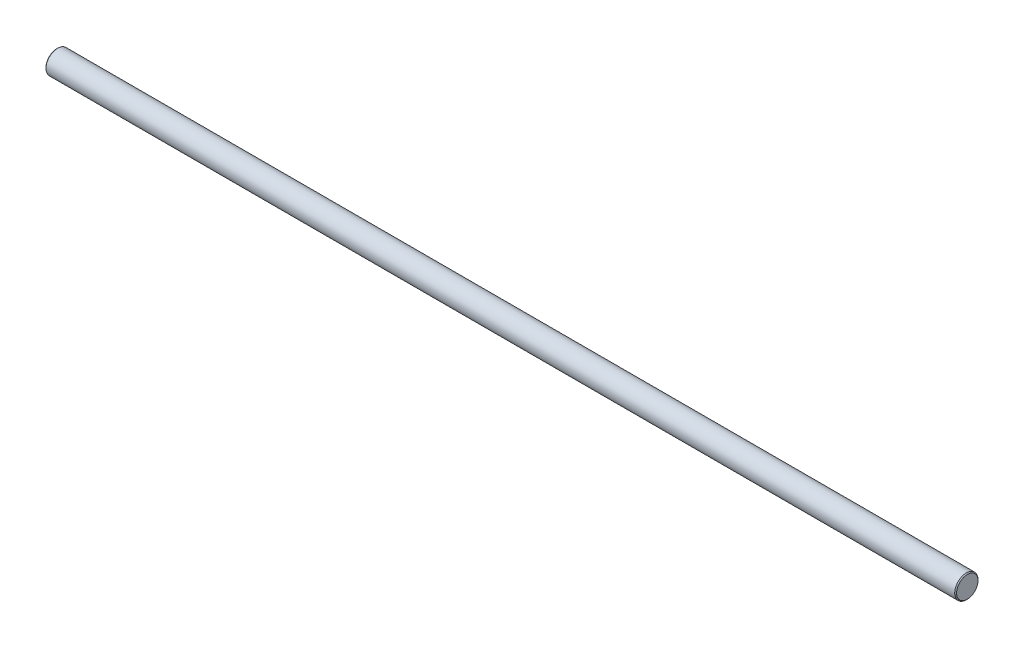
SolidWorks part; units mm, degrees
material "Alloy Steel"
ref_plane "Front Plane" through (0, 0, 0) normal (0, 0, 1) x (1, 0, 0)
ref_plane "Top Plane" through (0, 0, 0) normal (0, 1, 0) x (1, 0, 0)
ref_plane "Right Plane" through (0, 0, 0) normal (1, 0, 0) x (0, 0, -1)
sketch "Sketch1" plane through (0, 0, 0) normal (1, 0, 0) x (0, 0, -1)
  circle A0 centre (0, 0) radius 6.3437
  dimension "D1" = 12.6873
extrude "Boss-Extrude1" add sketch "Sketch1" along normal mid plane 495.3 contours A0
chamfer "Chamfer1" distance 0.508 angle 45 2 edges at (-247.65, 0, -6.3437) (247.65, 0, -6.3437)
